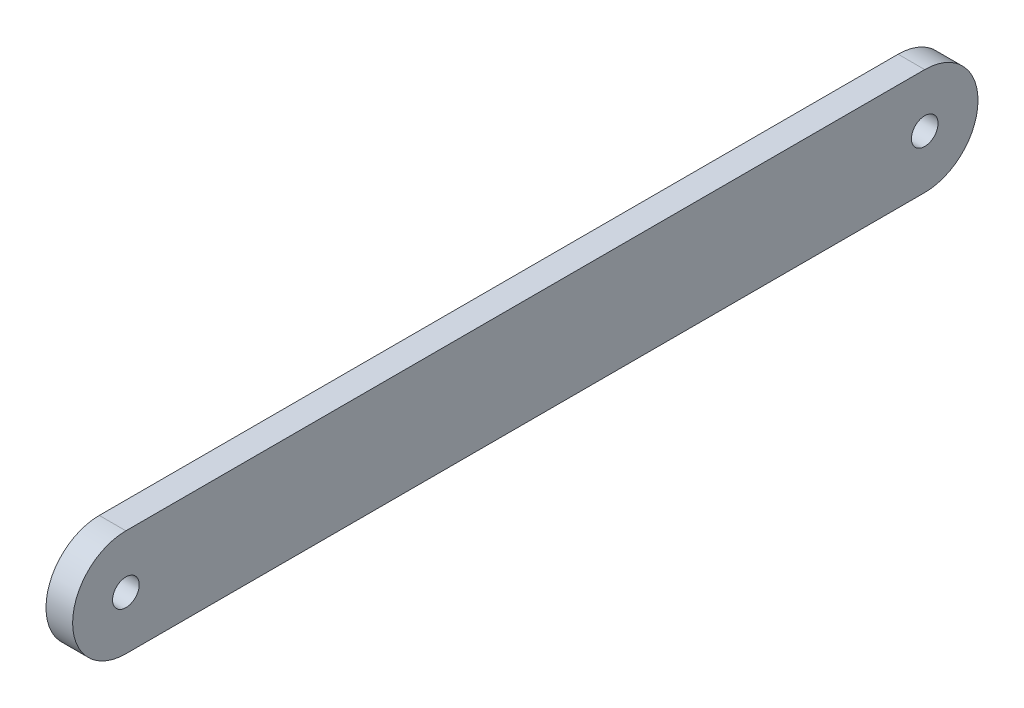
SolidWorks part; units mm, degrees
ref_plane "Front Plane" through (0, 0, 0) normal (0, 0, 1) x (1, 0, 0)
ref_plane "Top Plane" through (0, 0, 0) normal (0, 1, 0) x (1, 0, 0)
ref_plane "Right Plane" through (0, 0, 0) normal (1, 0, 0) x (0, 0, -1)
sketch "Sketch1" plane through (0, 0, 0) normal (1, 0, 0) x (0, 0, -1)
  line L0 (0, 10) -> (150, 10)
  line L1 (0, -10) -> (150, -10)
  circle A0 centre (0, 0) radius 2.5
  arc A1 (0, 10) -> (0, -10) centre (0, 0) ccw
  circle A2 centre (150, 0) radius 2.5
  arc A3 (150, -10) -> (150, 10) centre (150, 0) ccw
  dimension "D1" = 5
  dimension "D2" = 5
  dimension "D3" = 20
  dimension "D4" = 20
  dimension "D5" = 150
extrude "Boss-Extrude1" add sketch "Sketch1" along normal blind 5
